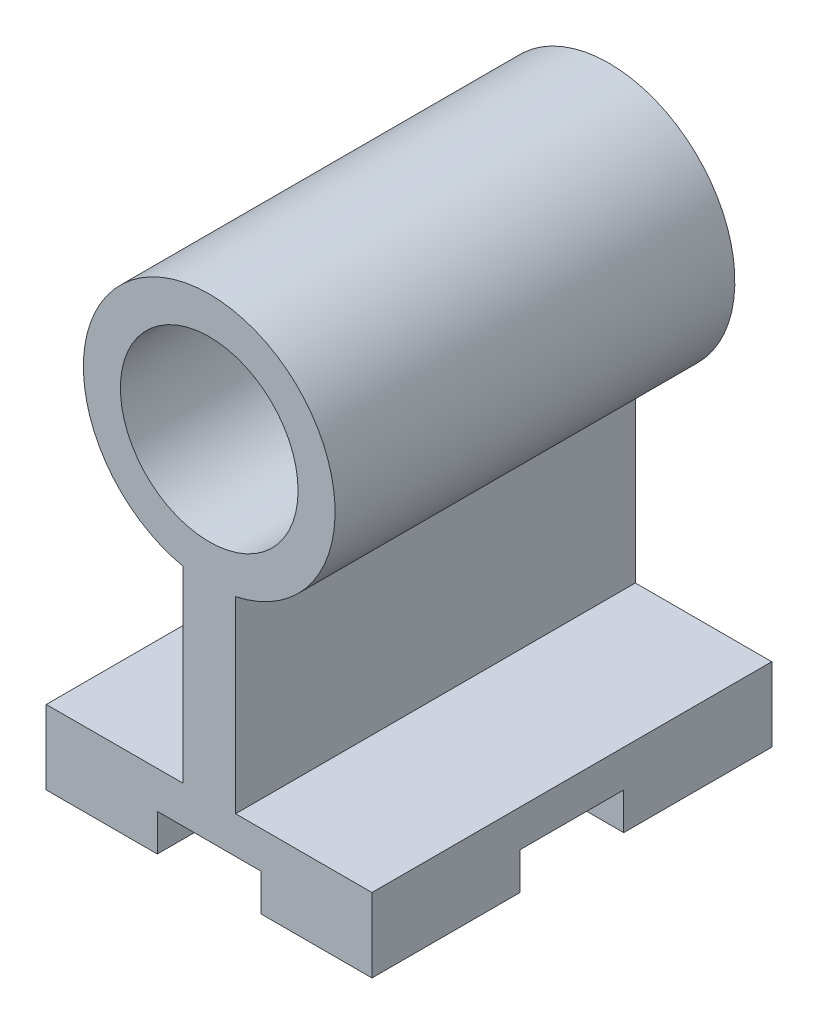
SolidWorks part; units mm, degrees
ref_plane "Front Plane" through (0, 0, 0) normal (0, 0, 1) x (1, 0, 0)
ref_plane "Top Plane" through (0, 0, 0) normal (0, 1, 0) x (1, 0, 0)
ref_plane "Right Plane" through (0, 0, 0) normal (1, 0, 0) x (0, 0, -1)
sketch "Sketch1" plane through (0, 0, 0) normal (0, 0, 1) x (1, 0, 0)
  line L0 (-22, 0) -> (-7, 0)
  line L1 (-22, 0) -> (-22, 10)
  line L2 (22, 0) -> (22, 10)
  line L3 (7, 0) -> (22, 0)
  line L4 (-3.5429, 35.4052) -> (-3.5429, 10.0237)
  line L6 (3.576, 35.4052) -> (3.576, 10)
  line L8 (3.576, 10) -> (22, 10)
  line L9 (-22, 10) -> (-3.5429, 10.0237)
  line L12 (-7, 0) -> (-7, 5)
  line L13 (-7, 5) -> (7, 5)
  line L14 (7, 0) -> (7, 5)
  circle A0 centre (0.0165, 52.0283) radius 12
  arc A1 (3.576, 35.4052) -> (-3.5429, 35.4052) centre (0.0165, 52.0283) ccw
  point P4 (0, 0)
  point P8 (-22, 0)
  point P15 (-22, 10)
  dimension "D1" = 15
  dimension "D2" = 24
  dimension "D3" = 17
  dimension "D4" = 7.1189
  dimension "D5" = 10
  dimension "D6" = 25.4052
  dimension "D7" = 42
extrude "Boss-Extrude1" add sketch "Sketch1" against normal blind 54
sketch "Sketch2" plane through (22, 0, 0) normal (1, 0, 0) x (0, 0, -1)
  line L1 (54, 0) -> (0, 0) construction
  line L3 (20, 0) -> (34, 0)
  line L8 (20, 0) -> (20, 5)
  line L9 (20, 5) -> (34, 5)
  line L10 (34, 0) -> (34, 5)
  dimension "D1" = 5
  dimension "D2" = 14
  dimension "D3" = 20
extrude "Cut-Extrude1" cut sketch "Sketch2" against normal blind 44
